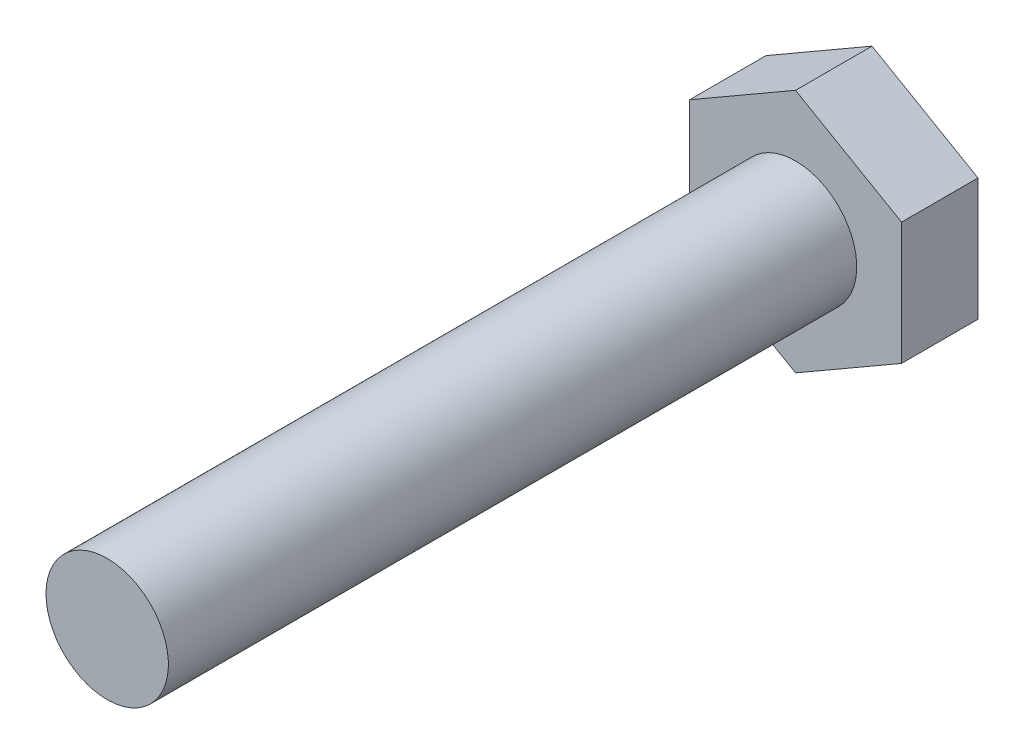
SolidWorks part; units mm, degrees
ref_plane "Front Plane" through (0, 0, 0) normal (0, 0, 1) x (1, 0, 0)
ref_plane "Top Plane" through (0, 0, 0) normal (0, 1, 0) x (1, 0, 0)
ref_plane "Right Plane" through (0, 0, 0) normal (1, 0, 0) x (0, 0, -1)
sketch "Sketch1" plane through (0, 0, 0) normal (0, 0, 1) x (1, 0, 0)
  line L1 (13.8564, 8) -> (0, 16)
  line L2 (0, 16) -> (-13.8564, 8)
  line L3 (-13.8564, 8) -> (-13.8564, -8)
  line L4 (-13.8564, -8) -> (0, -16)
  line L5 (0, -16) -> (13.8564, -8)
  line L6 (13.8564, -8) -> (13.8564, 8)
  circle A0 centre (0, 0) radius 13.8564 construction
  dimension "D1" = 16
extrude "Boss-Extrude1" add sketch "Sketch1" along normal blind 10
sketch "Sketch2" plane through (0, 0, 10) normal (0, 0, 1) x (1, 0, 0)
  circle A0 centre (0, 0) radius 8
extrude "Boss-Extrude2" add sketch "Sketch2" along normal blind 90
cosmetic thread "Cosmetic Thread1" parameters "D2"=13.797
